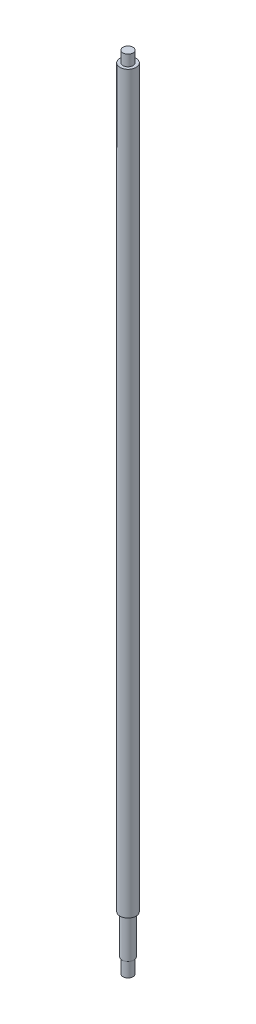
SolidWorks part; units mm, degrees
ref_plane "Front Plane" through (0, 0, 0) normal (0, 0, 1) x (1, 0, 0)
ref_plane "Top Plane" through (0, 0, 0) normal (0, 1, 0) x (1, 0, 0)
ref_plane "Right Plane" through (0, 0, 0) normal (1, 0, 0) x (0, 0, -1)
sketch "Sketch1" plane through (0, 0, 0) normal (0, 0, 1) x (1, 0, 0)
  line L0 (0, 0) -> (5, 0)
  line L1 (5, 0) -> (5, 15)
  line L2 (5, 15) -> (6, 15)
  line L3 (6, 15) -> (6, 54)
  line L4 (6, 54) -> (8, 54)
  line L5 (8, 54) -> (8, 789)
  line L6 (8, 789) -> (5, 789)
  line L7 (5, 789) -> (5, 800)
  line L8 (5, 800) -> (0, 800)
  line L9 (0, 800) -> (0, 0)
  line L10 (0, 0) -> (0, 1307.7459) construction
  point P7 (2.5, 0)
  point P13 (6, 34.5)
  dimension "D1" = 800
  dimension "D2" = 10
  dimension "D3" = 15
  dimension "D4" = 12
  dimension "D5" = 39
  dimension "D6" = 11
  dimension "D7" = 10
  dimension "D8" = 16
revolve "Revolve1" add sketch "Sketch1" angle 360 about L10
